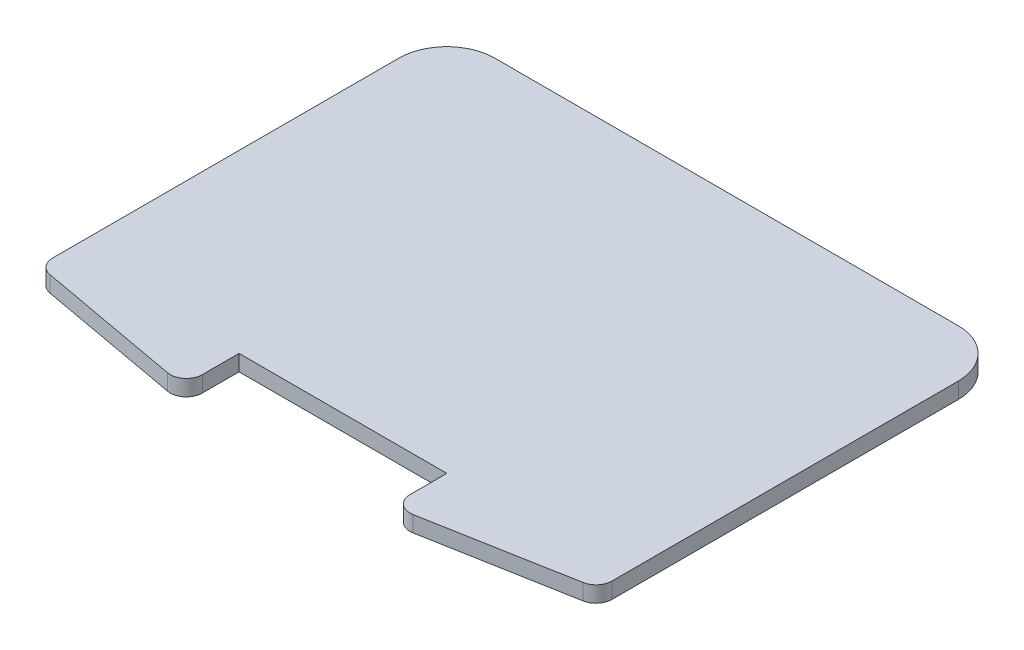
SolidWorks part; units mm, degrees
ref_plane "前视基准面" through (0, 0, 0) normal (0, 0, 1) x (1, 0, 0)
ref_plane "上视基准面" through (0, 0, 0) normal (0, 1, 0) x (1, 0, 0)
ref_plane "右视基准面" through (0, 0, 0) normal (1, 0, 0) x (0, 0, -1)
sketch "草图1" plane through (0, 0, 0) normal (0, 1, 0) x (1, 0, 0)
  line L1 (-17.5, 12.75) -> (17.5, 12.75)
  line L2 (-17.5, 12.75) -> (-17.5, -12.75)
  line L3 (-17.5, -12.75) -> (17.5, -12.75)
  line L4 (17.5, 12.75) -> (17.5, -12.75)
  line L5 (-17.5, 12.75) -> (17.5, -12.75) construction
  line L6 (-17.5, -12.75) -> (17.5, 12.75) construction
  point P0 (0, 0)
  dimension "D1" = 35
  dimension "D2" = 25.5
extrude "凸台-拉伸1" add sketch "草图1" along normal blind 1
sketch "草图2" plane through (0, 1, 0) normal (0, 1, 0) x (1, 0, 0)
  line L0 (-17.5, -12.75) -> (17.5, -12.75) construction
  line L1 (-17.5, 12.75) -> (-17.5, -12.75) construction
  line L3 (-17.5, -12.75) -> (-6.5, -14.75)
  line L4 (-6.5, -14.75) -> (-6.5, -12.75)
  line L5 (-17.5, -12.75) -> (-6.5, -12.75)
  line L6 (0, 12.75) -> (0, -12.75) construction
  line L7 (17.5, 12.75) -> (-17.5, 12.75) construction
  line L8 (17.5, -12.75) -> (6.5, -12.75)
  line L9 (6.5, -14.75) -> (6.5, -12.75)
  line L10 (17.5, -12.75) -> (6.5, -14.75)
  point P0 (-6.5, -12.75)
  point P1 (-6.5, -14.75)
  dimension "D1" = 11
  dimension "D2" = 2
extrude "凸台-拉伸2" add sketch "草图2" against normal blind 1
sketch "草图3" plane through (0, 1, 0) normal (0, 1, 0) x (1, 0, 0)
  line L0 (6.5, -12.75) -> (6.5, -14.75) construction
  line L1 (-6.5, -12.75) -> (6.5, -12.75)
  line L2 (-6.5, -12.75) -> (-6.5, -11.25)
  line L3 (-6.5, -11.25) -> (6.5, -11.25)
  line L4 (6.5, -12.75) -> (6.5, -11.25)
  dimension "D1" = 1.5
extrude "切除-拉伸1" cut sketch "草图3" against normal through all
fillet "圆角1" radius 3 2 edges at (17.5, 0.5, -12.75) (-17.5, 0.5, -12.75)
fillet "圆角2" radius 1 4 edges at (17.5, 0.5, 12.75) (6.5, 0.5, 14.75) (-6.5, 0.5, 14.75) (-17.5, 0.5, 12.75)
